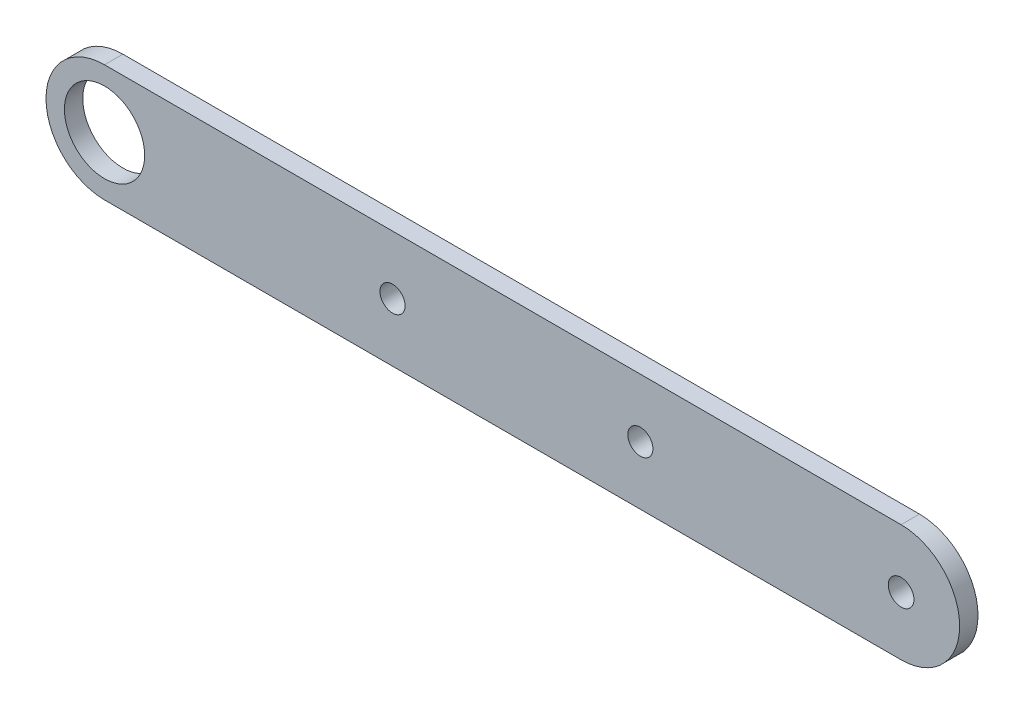
SolidWorks part; units mm, degrees
ref_plane "Plan de face" through (0, 0, 0) normal (0, 0, 1) x (1, 0, 0)
ref_plane "Plan de dessus" through (0, 0, 0) normal (0, 1, 0) x (1, 0, 0)
ref_plane "Plan de droite" through (0, 0, 0) normal (1, 0, 0) x (0, 0, -1)
sketch "Esquisse1" plane through (0, 0, 0) normal (0, 0, 1) x (1, 0, 0)
  line L0 (-130, 0) -> (0, 0) construction
  line L1 (-130, 9.55) -> (0, 9.55)
  line L2 (-130, -9.55) -> (0, -9.55)
  line L3 (-123.45, 2.05) -> (-83, 2.05) construction
  line L4 (-83, 2.05) -> (-42.55, 2.05) construction
  line L5 (-42.55, 2.05) -> (-2.1, 2.05) construction
  circle A0 centre (0, 0) radius 2.1
  circle A1 centre (-130, 0) radius 6.55
  arc A2 (-130, 9.55) -> (-130, -9.55) centre (-130, 0) ccw
  arc A3 (0, -9.55) -> (0, 9.55) centre (0, 0) ccw
  circle A4 centre (-83, 0) radius 2.05
  circle A5 centre (-42.55, 0) radius 2.05
  point P5 (-65, 0)
  point P10 (-130, 6.55)
  point P17 (-2.1, 0)
  point P20 (-123.45, 0)
  dimension "D1" = 13.1
  dimension "D4" = 4.1
  dimension "D5" = 4.2
  dimension "D2" = 130
  dimension "D3" = 3
extrude "Boss.-Extru.1" add sketch "Esquisse1" along normal blind 3
